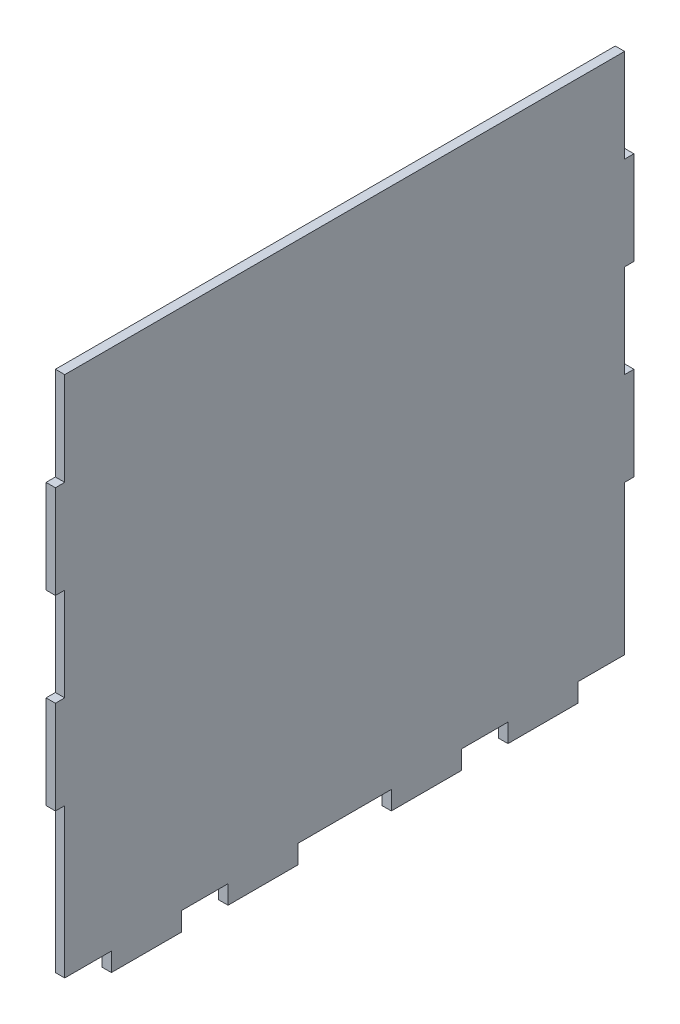
SolidWorks part; units mm, degrees
ref_plane "Front Plane" through (0, 0, 0) normal (0, 0, 1) x (1, 0, 0)
ref_plane "Top Plane" through (0, 0, 0) normal (0, 1, 0) x (1, 0, 0)
ref_plane "Right Plane" through (0, 0, 0) normal (1, 0, 0) x (0, 0, -1)
sketch "Sketch1" plane through (0, 0, 0) normal (1, 0, 0) x (0, 0, -1)
  line L0 (0, 55) -> (0, -55) construction
  line L1 (-60, -56) -> (-50, -56)
  line L2 (-60, -56) -> (-60, -24)
  line L3 (-60, 56) -> (60, 56)
  line L4 (60, -56) -> (60, -24)
  line L5 (-60, -56) -> (60, 56) construction
  line L6 (-60, 56) -> (60, -56) construction
  line L7 (60, 36) -> (62, 36)
  line L9 (60, 16) -> (62, 16)
  line L10 (62, 36) -> (62, 16)
  line L11 (60, -4) -> (62, -4)
  line L13 (60, -24) -> (62, -24)
  line L14 (62, -4) -> (62, -24)
  line L15 (-60, -24) -> (-62, -24)
  line L16 (-62, -4) -> (-62, -24)
  line L17 (-60, -4) -> (-62, -4)
  line L19 (-60, 16) -> (-62, 16)
  line L20 (-62, 36) -> (-62, 16)
  line L21 (-60, 36) -> (-62, 36)
  line L23 (-60, 36) -> (-60, 56)
  line L24 (-60, -4) -> (-60, 16)
  line L25 (60, -4) -> (60, 16)
  line L26 (60, 36) -> (60, 56)
  line L27 (-25, -56) -> (-25, -60)
  line L29 (-50, -56) -> (-50, -60)
  line L30 (-50, -60) -> (-35, -60)
  line L31 (-35, -56) -> (-35, -60)
  line L33 (-10, -56) -> (-10, -60)
  line L34 (-25, -60) -> (-10, -60)
  line L35 (50, -60) -> (35, -60)
  line L36 (35, -56) -> (35, -60)
  line L38 (50, -56) -> (50, -60)
  line L40 (10, -56) -> (10, -60)
  line L41 (25, -60) -> (10, -60)
  line L42 (25, -56) -> (25, -60)
  line L43 (-35, -56) -> (-25, -56)
  line L44 (-10, -56) -> (10, -56)
  line L45 (25, -56) -> (35, -56)
  line L46 (50, -56) -> (60, -56)
  point P0 (0, 0)
  dimension "D1" = 120
  dimension "D2" = 112
  dimension "D3" = 2
  dimension "D4" = 2
  dimension "D5" = 20
  dimension "D6" = 20
  dimension "D7" = 20
  dimension "D8" = 20
  dimension "D9" = 15
  dimension "D10" = 4
  dimension "D11" = 10
  dimension "D13" = 10
  dimension "D12" = 2
extrude "Boss-Extrude1" add sketch "Sketch1" along normal blind 2
